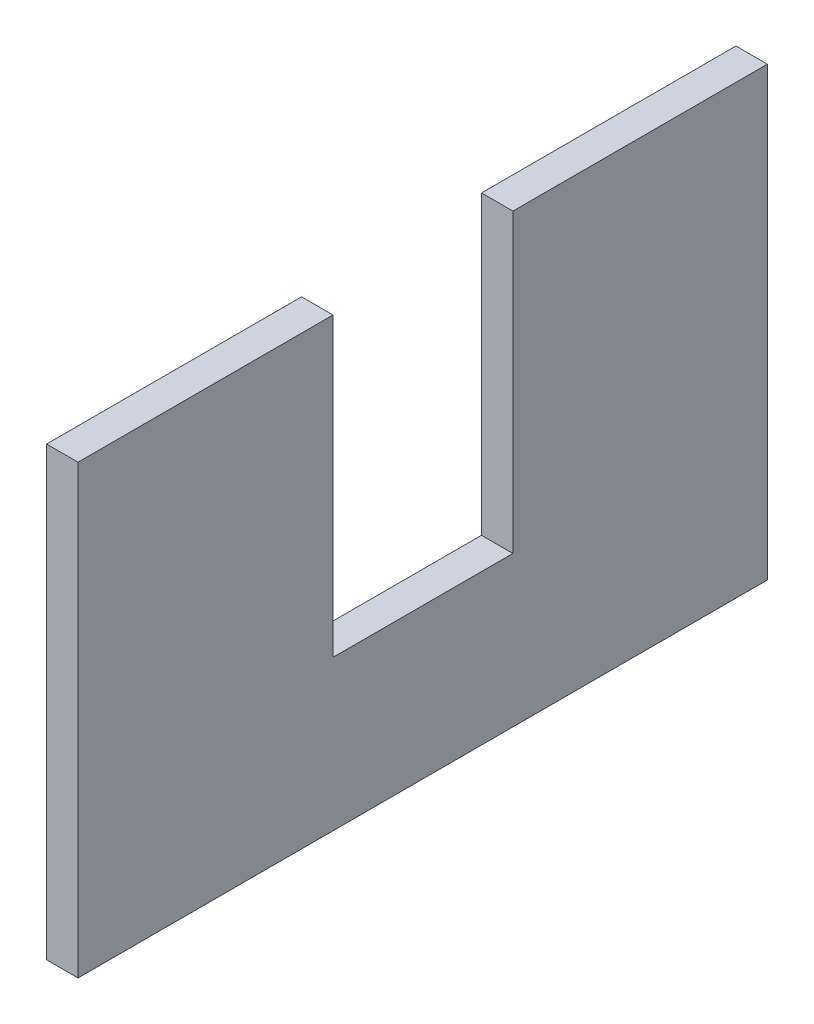
SolidWorks part; units mm, degrees
ref_plane "Alzado" through (0, 0, 0) normal (0, 0, 1) x (1, 0, 0)
ref_plane "Planta" through (0, 0, 0) normal (0, 1, 0) x (1, 0, 0)
ref_plane "Vista lateral" through (0, 0, 0) normal (1, 0, 0) x (0, 0, -1)
sketch "Croquis1" plane through (0, 0, 0) normal (1, 0, 0) x (0, 0, -1)
  line L0 (28.5918, 45.396) -> (69.0419, 45.396)
  line L1 (-40.5265, -25.604) -> (69.0419, -25.604)
  line L2 (-40.5265, -25.604) -> (-40.5265, 45.396)
  line L3 (-40.5265, 45.396) -> (0, 45.396)
  line L4 (69.0419, -25.604) -> (69.0419, 45.396)
  line L6 (0, 45.396) -> (0, -1.7264)
  line L7 (0, -1.7264) -> (28.5918, -1.7264)
  line L8 (28.5918, 45.396) -> (28.5918, -1.7264)
  dimension "D1" = 71
  dimension "D2" = 109.5685
extrude "Saliente-Extruir1" add sketch "Croquis1" along normal blind 5
